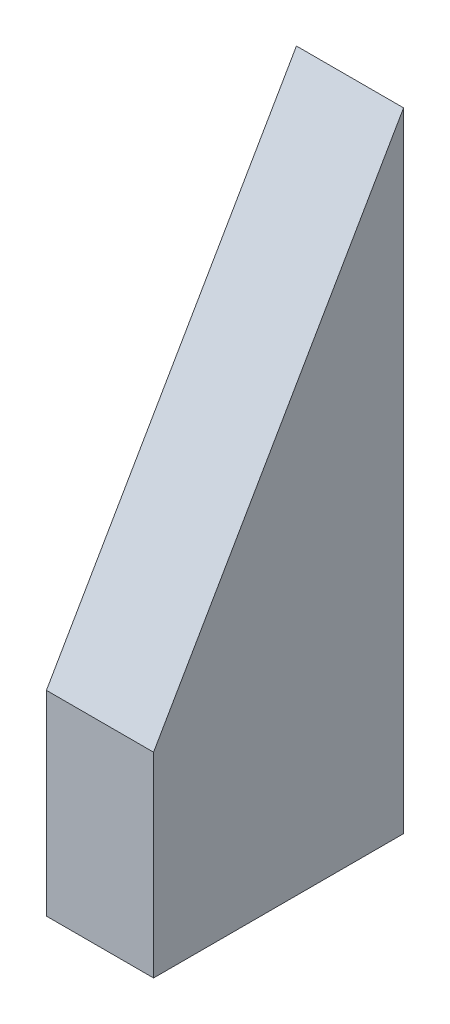
SolidWorks part; units mm, degrees
ref_plane "Front" through (0, 0, 0) normal (0, 0, 1) x (1, 0, 0)
ref_plane "Top" through (0, 0, 0) normal (0, 1, 0) x (1, 0, 0)
ref_plane "Right" through (0, 0, 0) normal (1, 0, 0) x (0, 0, -1)
sketch "Sketch1" plane through (0, 0, 0) normal (0, 1, 0) x (1, 0, 0)
  line L1 (-18.75, -43.75) -> (18.75, -43.75)
  line L2 (-18.75, -43.75) -> (-18.75, 43.75)
  line L3 (-18.75, 43.75) -> (18.75, 43.75)
  line L4 (18.75, -43.75) -> (18.75, 43.75)
  line L5 (-18.75, -43.75) -> (18.75, 43.75) construction
  line L6 (-18.75, 43.75) -> (18.75, -43.75) construction
  point P0 (0, 0)
  dimension "D1" = 87.5
  dimension "D2" = 37.5
extrude "Boss-Extrude1" add sketch "Sketch1" along normal blind 220
sketch "Sketch2" plane through (0, 0, 0) normal (1, 0, 0) x (0, 0, -1)
  line L0 (43.75, 220) -> (-43.75, 68.4456)
  line L1 (-43.75, 220) -> (-43.75, 0) construction
  line L2 (-43.75, 68.4456) -> (-43.75, 220)
  line L3 (-43.75, 220) -> (43.75, 220)
  dimension "D1" = 30
extrude "Cut-Extrude1" cut sketch "Sketch2" against normal through all both and the other way through all
